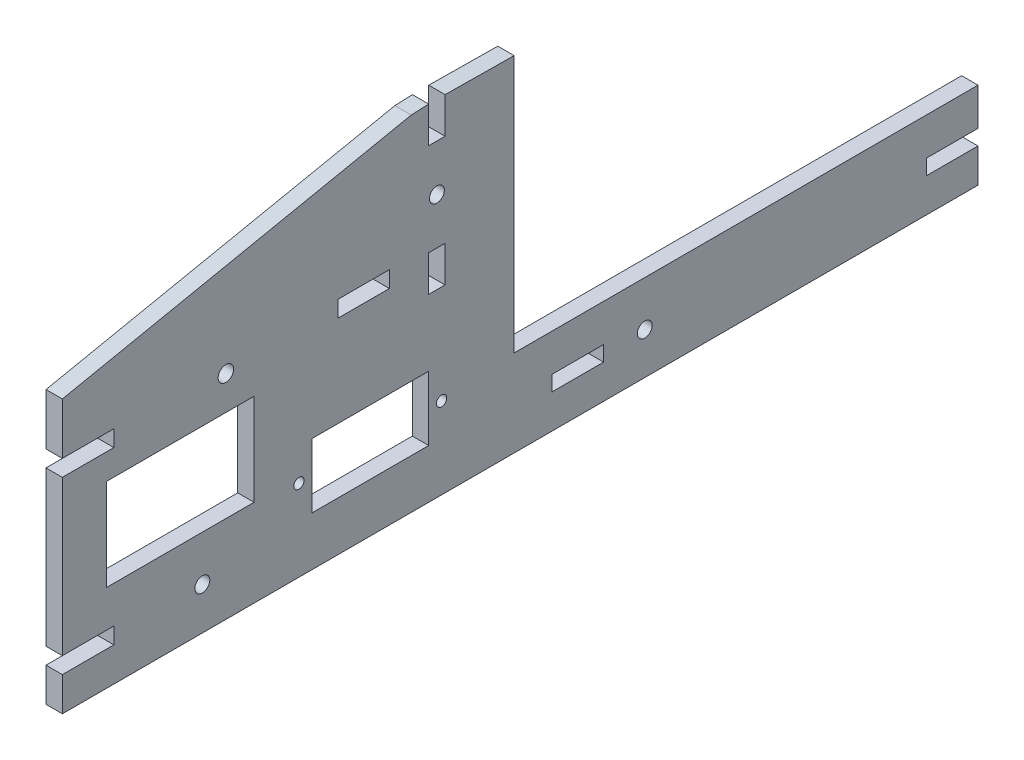
SolidWorks part; units mm, degrees
ref_plane "Front Plane" through (0, 0, 0) normal (0, 0, 1) x (1, 0, 0)
ref_plane "Top Plane" through (0, 0, 0) normal (0, 1, 0) x (1, 0, 0)
ref_plane "Right Plane" through (0, 0, 0) normal (1, 0, 0) x (0, 0, -1)
sketch "Sketch1" plane through (0, 0, 0) normal (1, 0, 0) x (0, 0, -1)
  line L0 (71.1977, -30.4388) -> (71.1977, -37.0367)
  line L1 (-106.5988, -27.2617) -> (-106.5988, 2.7383)
  line L2 (-96.5988, 5.9133) -> (-106.5988, 5.9133)
  line L3 (-106.5988, -37.0367) -> (71.1977, -37.0367)
  line L4 (61.1977, -30.4388) -> (61.1977, -27.4838)
  line L5 (61.1977, -27.4838) -> (71.1977, -27.4838)
  line L6 (-106.5988, -30.4367) -> (-106.5988, -37.0367)
  line L7 (71.1977, -30.4388) -> (61.1977, -30.4388)
  line L8 (71.1977, -27.4838) -> (71.1977, -20.2117)
  line L9 (-58.1618, -27.4838) -> (-35.4618, -27.4838)
  line L10 (-11.5107, -27.4838) -> (-1.5107, -27.4838)
  line L11 (-1.5107, -27.4838) -> (-1.5107, -30.4367)
  line L12 (-1.5107, -30.4367) -> (-11.5107, -30.4367)
  line L13 (-106.5988, -27.2617) -> (-96.5988, -27.2617)
  line L14 (-18.8656, -20.2117) -> (71.1977, -20.2117)
  line L15 (-106.5988, -30.4367) -> (-96.5988, -30.4367)
  line L16 (-96.5988, -27.2617) -> (-96.5988, -30.4367)
  line L17 (-11.5107, -30.4367) -> (-11.5107, -27.4838)
  line L18 (-18.8656, -20.2117) -> (-18.8656, 29.7883)
  line L19 (-38.8656, 29.7883) -> (-35.458, 29.9366)
  line L20 (-106.5988, 15.9133) -> (-38.8656, 29.7883)
  line L21 (-58.1618, -14.9838) -> (-35.4618, -14.9838)
  line L22 (-58.1618, -14.9838) -> (-58.1618, -27.4838)
  line L23 (-43.0988, 5.9133) -> (-53.0988, 5.9133)
  line L24 (-35.4618, -14.9838) -> (-35.4618, -27.4838)
  line L25 (-32.283, 29.9366) -> (-18.8656, 29.7883)
  line L26 (-35.458, 29.9366) -> (-35.458, 22.9366)
  line L27 (-35.458, 22.9366) -> (-32.283, 22.9366)
  line L28 (-32.283, 29.9366) -> (-32.283, 22.9366)
  line L29 (-35.4618, 4.9366) -> (-32.2868, 4.9366)
  line L30 (-35.4618, 4.9366) -> (-35.4618, -2.0634)
  line L31 (-35.4618, -2.0634) -> (-32.2868, -2.0634)
  line L32 (-32.2868, 4.9366) -> (-32.2868, -2.0634)
  line L33 (-43.0988, 5.9133) -> (-43.0988, 2.7383)
  line L34 (-43.0988, 2.7383) -> (-53.0988, 2.7383)
  line L35 (-53.0988, 5.9133) -> (-53.0988, 2.7383)
  line L37 (-96.5988, 2.7383) -> (-106.5988, 2.7383)
  line L38 (-96.5988, 5.9133) -> (-96.5988, 2.7383)
  line L39 (-106.5988, 5.9133) -> (-106.5988, 15.9133)
  line L40 (-98.074, -2.239) -> (-69.3724, -2.239)
  line L41 (-98.074, -2.239) -> (-98.074, -20.075)
  line L42 (-98.074, -20.075) -> (-69.3724, -20.075)
  line L43 (-69.3724, -2.239) -> (-69.3724, -20.075)
  circle A0 centre (-79.4188, -28.8492) radius 1.45
  circle A1 centre (6.4811, -28.9602) radius 1.4499
  circle A2 centre (-60.6618, -21.2338) radius 1
  circle A3 centre (-32.9618, -21.2338) radius 1
  circle A4 centre (-33.8705, 13.9366) radius 1.45
  circle A5 centre (-74.8488, 4.3258) radius 1.5
  point P4 (-96.5988, -28.8492)
  point P50 (-33.8705, 22.9366)
  point P51 (-53.0988, 4.3258)
  point P58 (-1.5107, -28.9602)
  dimension "D7" = 27.18
  dimension "D20" = 2.5
  dimension "D10" = 3.175
  dimension "D27" = 16
  dimension "D3" = 10
  dimension "D4" = 32
  dimension "D5" = 10
  dimension "D6" = 6.25
  dimension "D8" = 20
  dimension "D9" = 3.175
  dimension "D11" = 7.2721
  dimension "D12" = 10
  dimension "D13" = 2.5
  dimension "D14" = 30
  dimension "D15" = 10
  dimension "D16" = 6.5979
  dimension "D17" = 6.6
  dimension "D18" = 22.7
  dimension "D19" = 12.5
  dimension "D21" = 7
  dimension "D22" = 3.175
  dimension "D23" = 3.175
  dimension "D24" = 7
  dimension "D25" = 6.25
  dimension "D26" = 2.955
  dimension "D28" = 50
  dimension "D29" = 10
  dimension "D30" = 3.175
  dimension "D31" = 95.0882
  dimension "D32" = 16.825
  dimension "D34" = 31.75
extrude "Extrude1" add sketch "Sketch1" along normal blind 3.175
